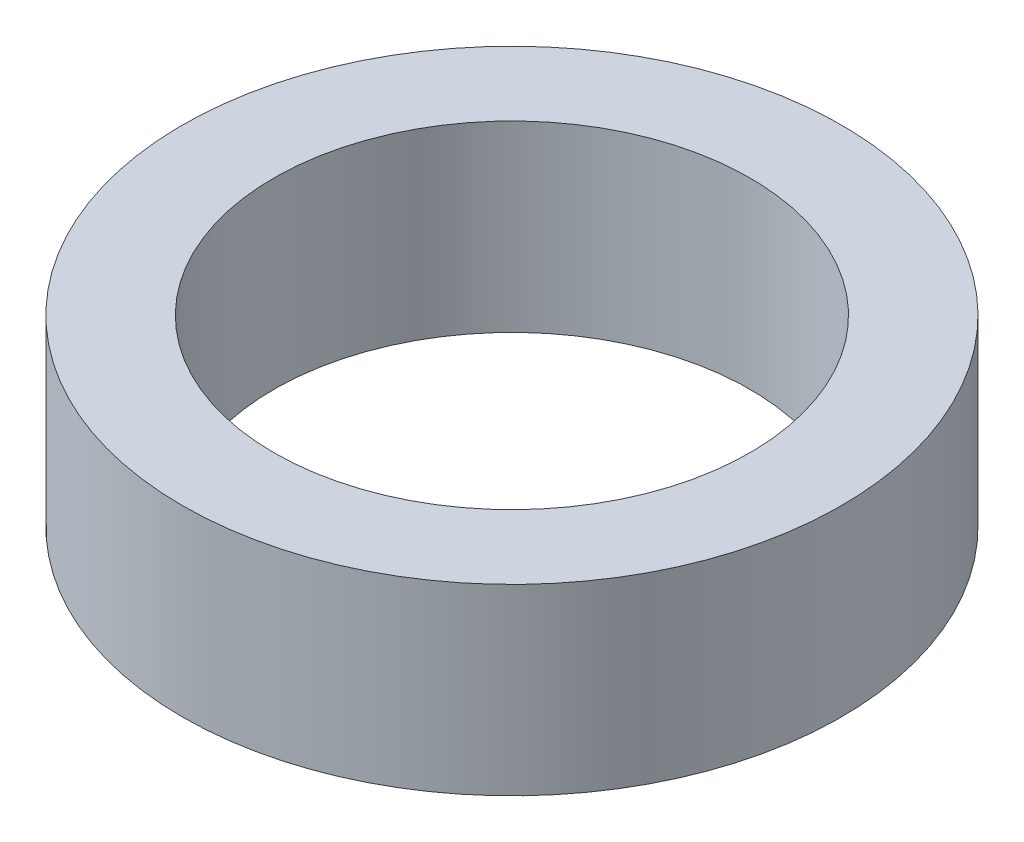
SolidWorks part; units mm, degrees
ref_plane "Front Plane" through (0, 0, 0) normal (0, 0, 1) x (1, 0, 0)
ref_plane "Top Plane" through (0, 0, 0) normal (0, 1, 0) x (1, 0, 0)
ref_plane "Right Plane" through (0, 0, 0) normal (1, 0, 0) x (0, 0, -1)
sketch "Sketch1" plane through (0, 0, 0) normal (0, 1, 0) x (1, 0, 0)
  circle A0 centre (0, 0) radius 6.5
  circle A1 centre (0, 0) radius 9
  dimension "D1" = 13
  dimension "D2" = 18
extrude "Boss-Extrude1" add sketch "Sketch1" along normal blind 5
